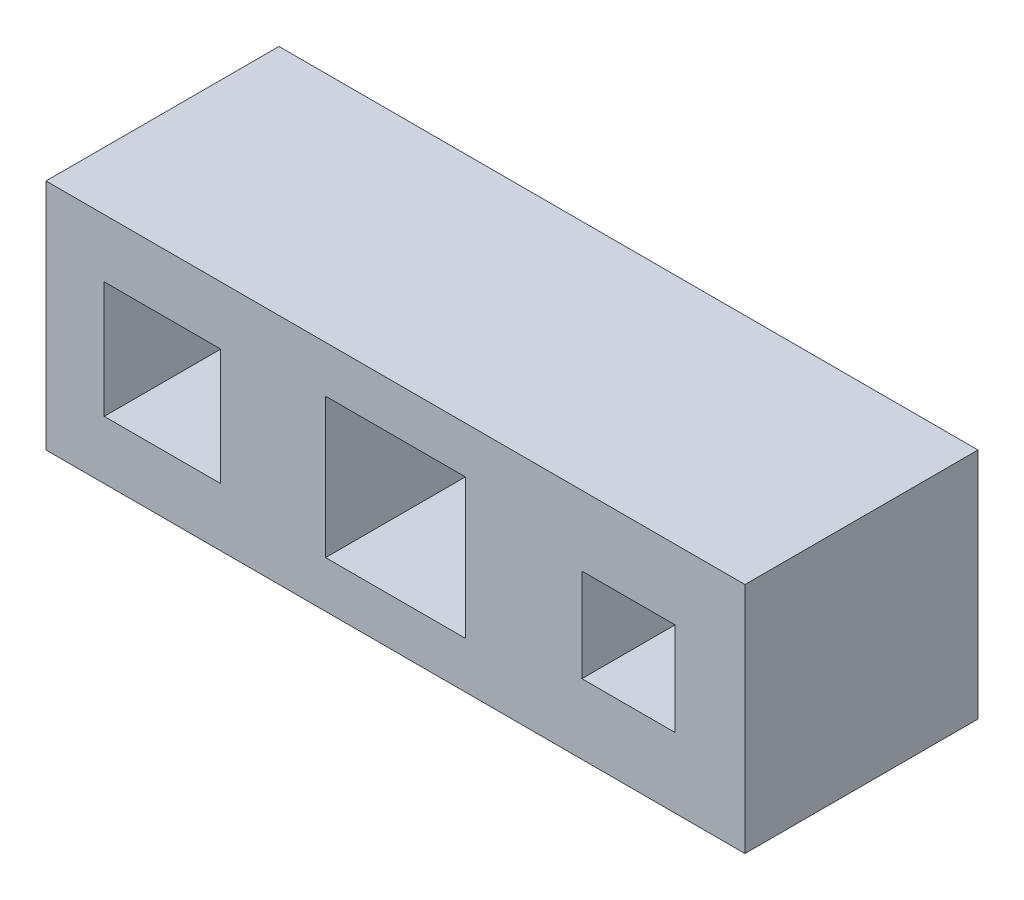
SolidWorks part; units mm, degrees
ref_plane "Front Plane" through (0, 0, 0) normal (0, 0, 1) x (1, 0, 0)
ref_plane "Top Plane" through (0, 0, 0) normal (0, 1, 0) x (1, 0, 0)
ref_plane "Right Plane" through (0, 0, 0) normal (1, 0, 0) x (0, 0, -1)
sketch "Sketch1" plane through (0, 0, 0) normal (0, 0, 1) x (1, 0, 0)
  line L1 (0, 0) -> (5, 0)
  line L2 (0, 0) -> (0, 5)
  line L3 (0, 5) -> (5, 5)
  line L5 (1.25, 1.25) -> (3.75, 1.25)
  line L6 (1.25, 1.25) -> (1.25, 3.75)
  line L7 (1.25, 3.75) -> (3.75, 3.75)
  line L8 (3.75, 1.25) -> (3.75, 3.75)
  line L9 (5, 5) -> (15, 5)
  line L11 (5, 0) -> (15, 0)
  line L12 (15, 5) -> (15, 0)
  line L13 (13.5, 3.5) -> (11.5, 3.5)
  line L14 (13.5, 3.5) -> (13.5, 1.5)
  line L15 (13.5, 1.5) -> (11.5, 1.5)
  line L16 (11.5, 3.5) -> (11.5, 1.5)
  line L17 (9, 4) -> (6, 4)
  line L18 (9, 4) -> (9, 1)
  line L19 (9, 1) -> (6, 1)
  line L20 (6, 4) -> (6, 1)
  dimension "D3" = 1.25
  dimension "D1" = 5
  dimension "D2" = 5
  dimension "D4" = 1.25
  dimension "D5" = 2.5
  dimension "D6" = 2.5
  dimension "D7" = 10
  dimension "D8" = 1.5
  dimension "D9" = 1.5
  dimension "D10" = 1
  dimension "D11" = 2.25
  dimension "D12" = 3
  dimension "D13" = 2
  dimension "D14" = 2.5
extrude "Boss-Extrude1" add sketch "Sketch1" along normal blind 5
